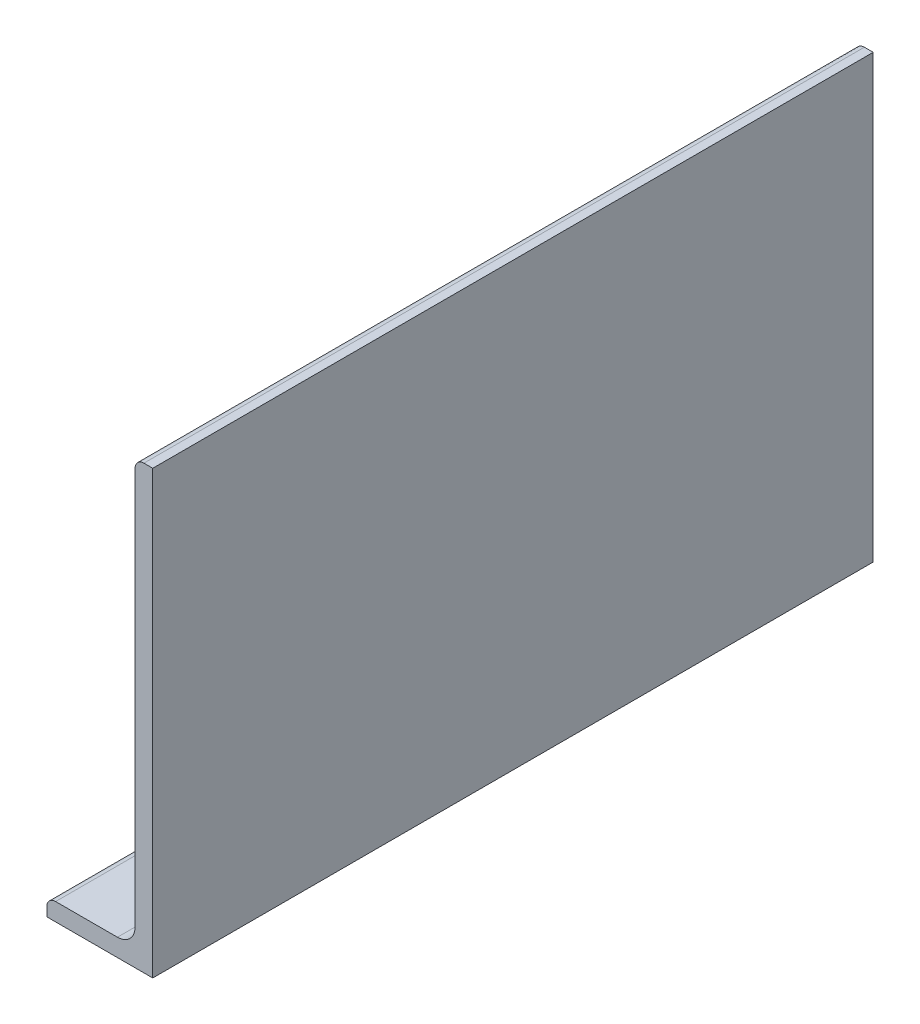
SolidWorks part; units mm, degrees
ref_plane "Front Plane" through (0, 0, 0) normal (0, 0, 1) x (1, 0, 0)
ref_plane "Top Plane" through (0, 0, 0) normal (0, 1, 0) x (1, 0, 0)
ref_plane "Right Plane" through (0, 0, 0) normal (1, 0, 0) x (0, 0, -1)
sketch "Sketch1" plane through (0, 0, 0) normal (0, 0, 1) x (1, 0, 0)
  line L0 (1156.0194, -193.2477) -> (1156.0194, -243.2477)
  line L1 (1156.0194, -243.2477) -> (1144.0194, -243.2477)
  line L2 (1144.0194, -243.2477) -> (1144.0194, -241.2477)
  line L3 (1144.0194, -241.2477) -> (1154.0194, -241.2477)
  line L4 (1154.0194, -241.2477) -> (1154.0194, -193.2477)
  line L5 (1154.0194, -193.2477) -> (1156.0194, -193.2477)
  dimension "D1" = 50
  dimension "D2" = 12
  dimension "D3" = 2
  dimension "D4" = 2
extrude "Boss-Extrude1" add sketch "Sketch1" along normal blind 81.6
fillet "Fillet1" radius 1 2 edges at (1144.0194, -241.2477, 40.8) (1154.0194, -193.2477, 40.8)
fillet "Fillet2" radius 2 1 edges at (1154.0194, -241.2477, 40.8)
sketch "Sketch2" plane through (0, -241.2477, 0) normal (0, 1, 0) x (1, 0, 0)
  line L0 (1152.0194, -81.6) -> (1145.0194, -81.6) construction
  line L1 (1152.0194, 0) -> (1145.0194, 0) construction
  line L2 (1144.0194, -81.6) -> (1144.0194, 0) construction
  circle A0 centre (1148.5194, -61.6) radius 1.6
  circle A1 centre (1148.5194, -20) radius 1.6
  dimension "D1" = 3.2
  dimension "D2" = 3.2
  dimension "D3" = 20
  dimension "D4" = 20
  dimension "D5" = 4.5
  dimension "D6" = 4.5
extrude "Cut-Extrude1" cut sketch "Sketch2" against normal through all
